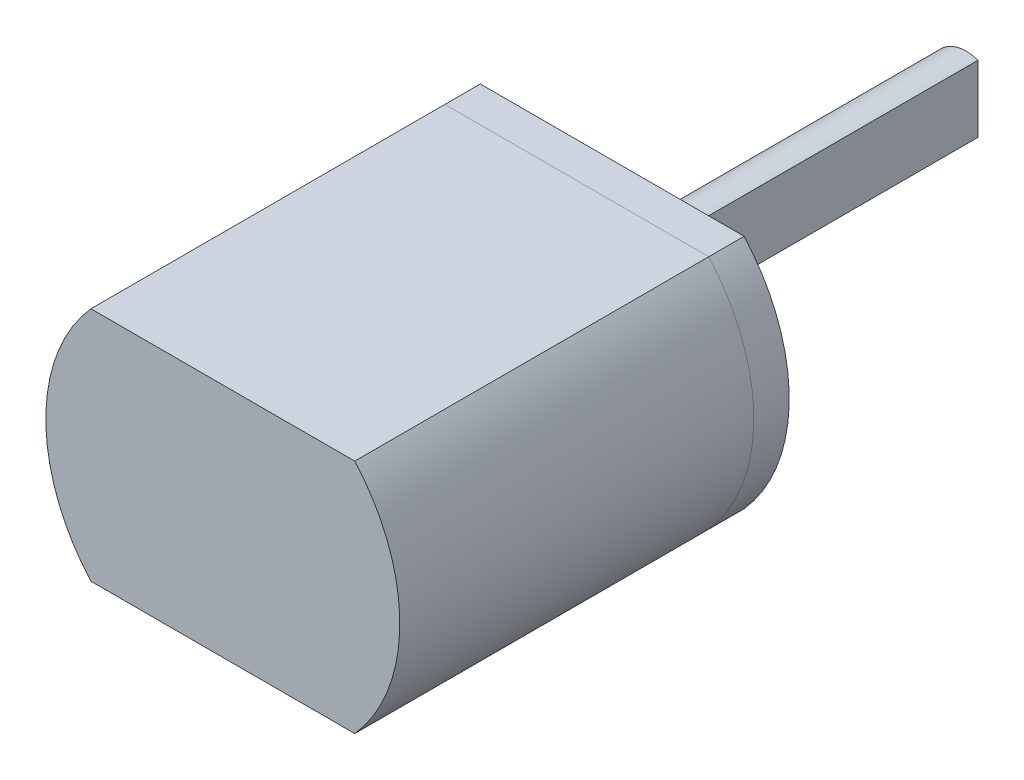
SolidWorks part; units mm, degrees
ref_plane "Front Plane" through (0, 0, 0) normal (0, 0, 1) x (1, 0, 0)
ref_plane "Top Plane" through (0, 0, 0) normal (0, 1, 0) x (1, 0, 0)
ref_plane "Right Plane" through (0, 0, 0) normal (1, 0, 0) x (0, 0, -1)
sketch "Sketch1" plane through (0, 0, 0) normal (0, 0, 1) x (1, 0, 0)
  line L1 (-5.5902, -5) -> (5.5902, -5)
  line L3 (-5.5902, 5) -> (5.5902, 5)
  line L5 (-13.9877, -5) -> (13.9877, 5) construction
  line L6 (-13.9877, 5) -> (13.9877, -5) construction
  arc A0 (-5.5902, 5) -> (-5.5902, -5) centre (0, 0) ccw
  arc A1 (5.5902, -5) -> (5.5902, 5) centre (0, 0) ccw
  dimension "D1" = 10
  dimension "D2" = 15
  dimension "D3" = 5
extrude "Boss-Extrude1" add sketch "Sketch1" along normal blind 15
sketch "Sketch2" plane through (0, 0, 0) normal (0, 0, -1) x (-1, 0, 0)
  line L0 (5.5902, -5) -> (-5.5902, -5) construction
  line L1 (-5.5902, 5) -> (5.5902, 5) construction
  line L2 (5.5902, -5) -> (-5.5902, -5)
  line L3 (-5.5902, 5) -> (5.5902, 5)
  arc A0 (-5.5902, 5) -> (-5.5902, -5) centre (0, 0) ccw construction
  arc A1 (-5.5902, 5) -> (-5.5902, -5) centre (0, 0) ccw
  arc A2 (5.5902, -5) -> (5.5902, 5) centre (0, 0) ccw construction
  arc A3 (5.5902, -5) -> (5.5902, 5) centre (0, 0) ccw
extrude "Boss-Extrude2" add sketch "Sketch2" along normal blind 1.5 separate body
sketch "Sketch3" plane through (0, 0, -1.5) normal (0, 0, -1) x (-1, 0, 0)
  line L0 (0, 5) -> (0, -5) construction
  line L1 (5.5902, 5) -> (-5.5902, 5) construction
  line L2 (-5.5902, -5) -> (5.5902, -5) construction
  line L3 (-0.5, -1.4142) -> (-0.5, 1.4142)
  arc A0 (-0.5, -1.4142) -> (-0.5, 1.4142) centre (0, 0) ccw
  dimension "D1" = 3
  dimension "D2" = 0.5
extrude "Boss-Extrude3" add sketch "Sketch3" along normal blind 15
